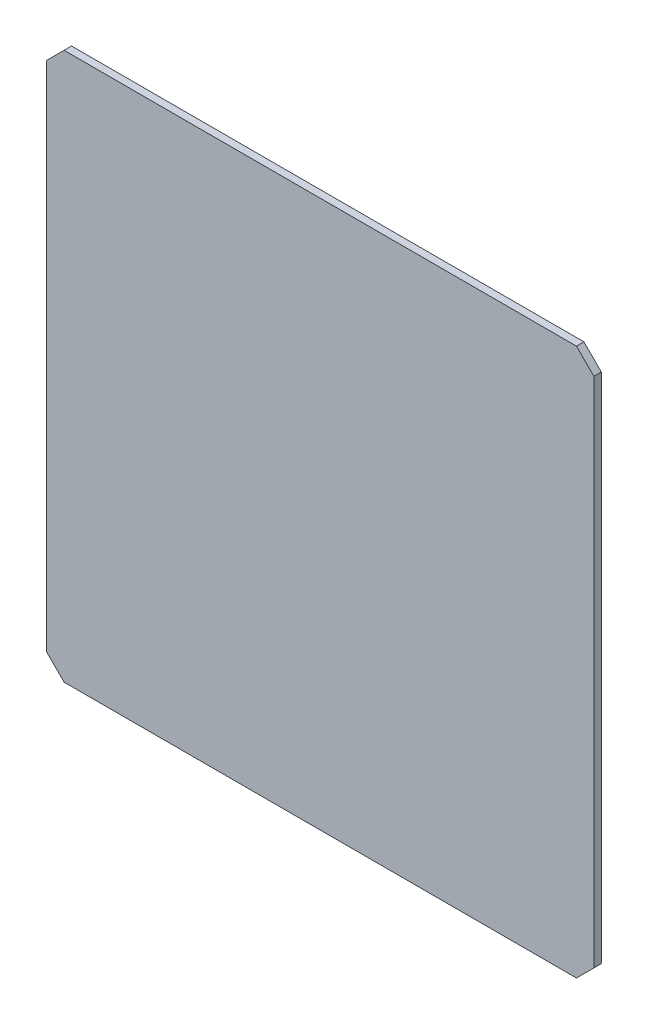
SolidWorks part; units mm, degrees
ref_plane "Front Plane" through (0, 0, 0) normal (0, 0, 1) x (1, 0, 0)
ref_plane "Top Plane" through (0, 0, 0) normal (0, 1, 0) x (1, 0, 0)
ref_plane "Right Plane" through (0, 0, 0) normal (1, 0, 0) x (0, 0, -1)
sketch "Sketch1" plane through (0, 0, 0) normal (0, 0, 1) x (1, 0, 0)
  line L5 (0, 0) -> (220, 0)
  line L6 (0, 0) -> (0, 220)
  line L7 (0, 220) -> (220, 220)
  line L8 (220, 0) -> (220, 220)
  dimension "D1" = 220
  dimension "D2" = 220
extrude "Boss-Extrude1" add sketch "Sketch1" against normal blind 3
chamfer "Chamfer1" distance 7 angle 45 4 edges at (0, 0, -1.5) (220, 0, -1.5) (220, 220, -1.5) (0, 220, -1.5)
